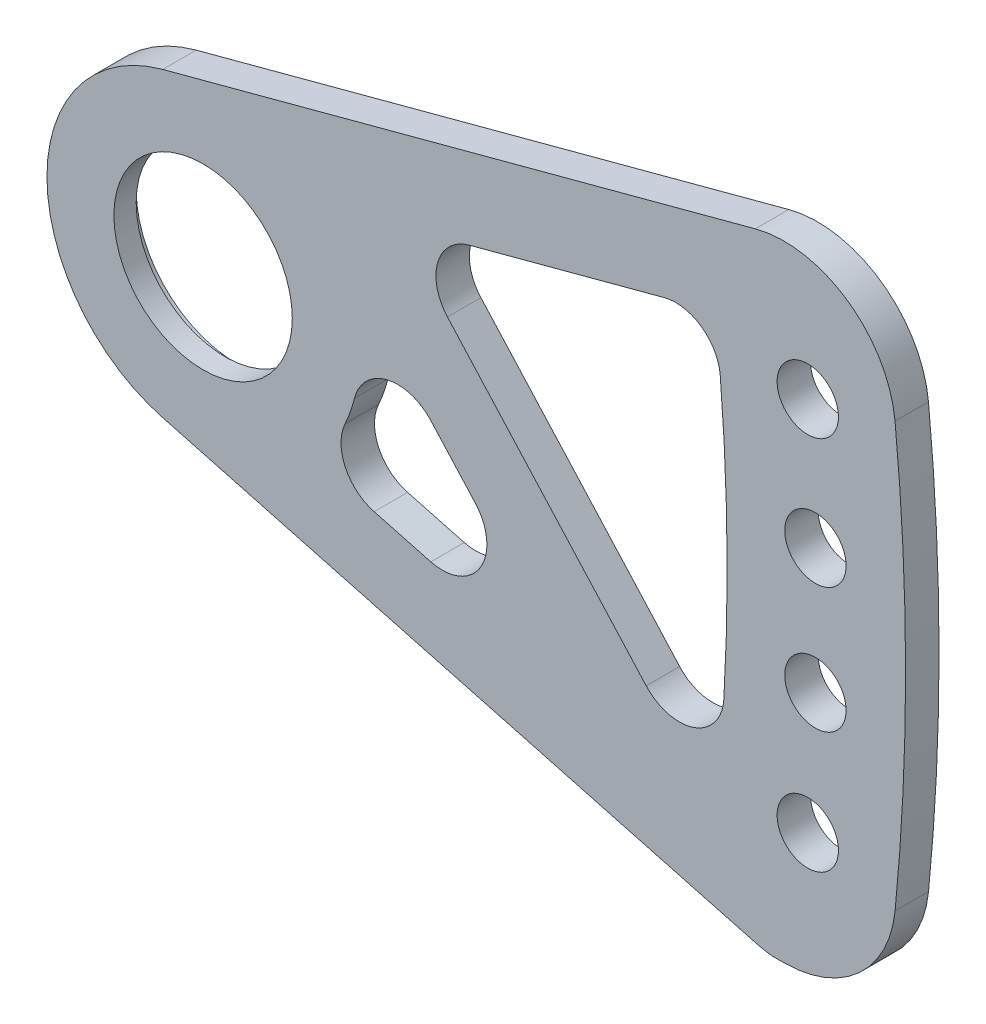
SolidWorks part; units mm, degrees
material "Сплав 2024"
ref_plane "Спереди" through (0, 0, 0) normal (0, 0, 1) x (1, 0, 0)
ref_plane "Сверху" through (0, 0, 0) normal (0, 1, 0) x (1, 0, 0)
ref_plane "Справа" through (0, 0, 0) normal (1, 0, 0) x (0, 0, -1)
sketch "Эскиз1" plane through (0, 0, 0) normal (0, 0, 1) x (1, 0, 0)
  line L0 (-31.9542, -25) -> (253.1565, -25) construction
  line L1 (9, 35.6094) -> (9, -47.5785) construction
  line L2 (-39.2405, -28) -> (262.4545, -28) construction
  line L3 (-31.9542, -22) -> (262.4545, -22) construction
  line L4 (-9.5085, -3.0964) -> (-1.3987, -28)
  line L5 (8.3266, 5.5379) -> (20.6752, -13.0291)
  line L6 (-26.4187, 0) -> (187.6558, 0) construction
  line L7 (121.0002, 11.4893) -> (83.7656, -14.4365)
  line L8 (63.7181, -22) -> (35.7314, -22)
  line L9 (0, 0) -> (183.9142, 5.6191) construction
  line L10 (0, 0) -> (183.9142, -5.6191) construction
  line L11 (0, 0) -> (183.2281, -16.8363) construction
  line L12 (0, 0) -> (183.2281, 16.8363) construction
  line L13 (125.388, 13.526) -> (189.5368, 30.6561)
  line L14 (-1.3987, -28) -> (189.9474, -28)
  line L15 (40.5, -17.0585) -> (40.5, -35.954) construction
  line L16 (72, -17.0585) -> (72, -35.954) construction
  line L17 (20.6752, -13.0291) -> (35.7314, -22)
  line L18 (83.7656, -14.4365) -> (63.7181, -22)
  arc A0 (8.3266, 5.5379) -> (-9.5085, -3.0964) centre (0, 0) ccw
  circle A1 centre (129, 0) radius 8
  arc A2 (125.388, 13.526) -> (121.0002, 11.4893) centre (129, 0) ccw
  circle A3 centre (0, 0) radius 184 construction
  arc A4 (189.9474, -28) -> (189.5368, 30.6561) centre (0, 0) ccw
  dimension "D1" = 20
  dimension "D2" = 25
  dimension "D3" = 9
  dimension "D6" = 16
  dimension "D8" = 28
  dimension "D9" = 368
  dimension "D10" = 31.5
  dimension "D16" = 192
  dimension "D4" = 6
  dimension "D5" = 3
  dimension "D7" = 129
  dimension "D11" = 3.5
  dimension "D12" = 3.5
  dimension "D13" = 3.5
  dimension "D14" = 1.75
  dimension "D15" = 31.5
extrude "Бобышка-Вытянуть1" add sketch "Эскиз1" along normal blind 3
hole_wizard "Отверстие с зазором M31" positions "Эскиз3" profile "Эскиз2" hole size "M3" standard "Ansi Metric" end condition through all
sketch "Эскиз3" plane through (0, 0, 3) normal (0, 0, 1) x (1, 0, 0)
  line L0 (-31.9542, -25) -> (253.1565, -25) construction
  line L1 (9, 35.6094) -> (9, -47.5785) construction
  line L2 (40.5, -17.0585) -> (40.5, -35.954) construction
  line L3 (72, -17.0585) -> (72, -35.954) construction
  point P0 (9, -25)
  point P6 (40.5, -25)
  point P10 (72, -25)
sketch "Эскиз2" plane through (9, -25, 3) normal (1, 0, 0) x (0, -1, 0)
  line L0 (0, 0) -> (0, 3)
  line L1 (0, 3) -> (1.7, 3)
  line L2 (1.7, 3) -> (1.7, 0)
  line L5 (1.7, 0) -> (0, 0)
  line L11 (0, -6.35) -> (0, 107.95) construction
  dimension "Диаметр сквозного отверстия" = 3.4
  dimension "Глубина сквозного отверстия" = 3
hole_wizard "Отверстие с зазором M51" positions "Эскиз5" profile "Эскиз4" hole size "M5" standard "Ansi Metric" end condition through all
sketch "Эскиз5" plane through (0, 0, 3) normal (0, 0, 1) x (1, 0, 0)
  point P2 (0, 0)
sketch "Эскиз4" plane through (0, 0, 3) normal (1, 0, 0) x (0, -1, 0)
  line L0 (0, 0) -> (0, 3)
  line L1 (0, 3) -> (2.75, 3)
  line L2 (2.75, 3) -> (2.75, 0)
  line L5 (2.75, 0) -> (0, 0)
  line L11 (0, -6.35) -> (0, 107.95) construction
  dimension "Диаметр сквозного отверстия" = 5.5
  dimension "Глубина сквозного отверстия" = 3
hole_wizard "Отверстие с зазором M52" positions "Эскиз7" profile "Эскиз6" hole size "M5" standard "Ansi Metric" end condition through all
sketch "Эскиз7" plane through (0, 0, 3) normal (0, 0, 1) x (1, 0, 0)
  point P0 (183.2281, 16.8363)
  point P3 (183.9142, 5.6191)
  point P6 (183.9142, -5.6191)
  point P9 (183.2281, -16.8363)
sketch "Эскиз6" plane through (183.2281, 16.8363, 3) normal (1, 0, 0) x (0, -1, 0)
  line L0 (0, 0) -> (0, 3)
  line L1 (0, 3) -> (2.75, 3)
  line L2 (2.75, 3) -> (2.75, 0)
  line L5 (2.75, 0) -> (0, 0)
  line L11 (0, -6.35) -> (0, 107.95) construction
  dimension "Диаметр сквозного отверстия" = 5.5
  dimension "Глубина сквозного отверстия" = 3
fillet "Скругление1" radius 10 6 edges at (35.7314, -22, 1.5) (20.6752, -13.0291, 1.5) (63.7181, -22, 1.5) (83.7656, -14.4365, 1.5) (189.9474, -28, 1.5) (189.5368, 30.6561, 1.5)
fillet "Скругление2" radius 5 1 edges at (-1.3987, -28, 1.5)
sketch "Эскиз8" plane through (0, 0, 3) normal (0, 0, 1) x (1, 0, 0)
  line L0 (138.9079, 9.8911) -> (175.4042, 19.6369)
  line L1 (178.5224, 27.7149) -> (125.388, 13.526) construction
  line L2 (142.9717, -0.889) -> (175.2463, -21)
  line L3 (175.2463, -21) -> (132.5, -21)
  line L4 (2.2315, -28) -> (181.1077, -28) construction
  line L5 (115.0501, -1.1834) -> (86.5894, -21)
  line L6 (121.0002, 11.4893) -> (84.7863, -13.7258) construction
  line L8 (125.5, -13.5554) -> (125.5, -21)
  line L9 (132.5, -13.5554) -> (132.5, -21)
  line L10 (138.9079, 9.8911) -> (176.0039, -13.2243)
  line L11 (125.5, -21) -> (86.5894, -21)
  arc A0 (115.0501, -1.1834) -> (125.5, -13.5554) centre (129, 0) ccw
  arc A1 (125.388, 13.526) -> (121.0002, 11.4893) centre (129, 0) ccw construction
  arc A2 (176.0039, -13.2243) -> (175.4042, 19.6369) centre (0, 0) ccw
  arc A3 (132.5, -13.5554) -> (142.9717, -0.889) centre (129, 0) ccw
  dimension "D2" = 353
  dimension "D1" = 7
  dimension "D3" = 7
  dimension "D4" = 7
  dimension "D5" = 7
  dimension "D6" = 3.5
  dimension "D7" = 7
extrude "Вырез-Вытянуть1" [suppressed] cut sketch "Эскиз8" against normal through all
fillet "Скругление3" [suppressed] radius 4
sketch "Эскиз9" plane through (0, 0, 0) normal (0, 0, -1) x (-1, 0, 0)
  circle A0 centre (-129, 0) radius 9
  dimension "D1" = 18
extrude "Вырез-Вытянуть2" cut sketch "Эскиз9" against normal blind 1
sketch "Эскиз10" plane through (0, 0, 3) normal (0, 0, 1) x (1, 0, 0)
  line L0 (6.5, -25) -> (11.5, -25) construction
  line L1 (6.5, -23.3) -> (11.5, -23.3)
  line L2 (6.5, -26.7) -> (11.5, -26.7)
  line L3 (38, -25) -> (43, -25) construction
  line L4 (38, -23.3) -> (43, -23.3)
  line L5 (38, -26.7) -> (43, -26.7)
  line L6 (69.5, -25) -> (74.5, -25) construction
  line L7 (69.5, -23.3) -> (74.5, -23.3)
  line L8 (69.5, -26.7) -> (74.5, -26.7)
  arc A0 (6.5, -23.3) -> (6.5, -26.7) centre (6.5, -25) ccw
  arc A1 (11.5, -26.7) -> (11.5, -23.3) centre (11.5, -25) ccw
  circle A2 centre (9, -25) radius 1.7 construction
  arc A3 (38, -23.3) -> (38, -26.7) centre (38, -25) ccw
  arc A4 (43, -26.7) -> (43, -23.3) centre (43, -25) ccw
  circle A5 centre (40.5, -25) radius 1.7 construction
  arc A6 (69.5, -23.3) -> (69.5, -26.7) centre (69.5, -25) ccw
  arc A7 (74.5, -26.7) -> (74.5, -23.3) centre (74.5, -25) ccw
  circle A8 centre (72, -25) radius 1.7 construction
  point P2 (9, -25)
  point P12 (40.5, -25)
  point P22 (72, -25)
  dimension "D1" = 5
  dimension "D2" = 5
  dimension "D3" = 5
extrude "Вырез-Вытянуть3" cut sketch "Эскиз10" against normal through all
sketch "Эскиз11" plane through (0, 0, 0) normal (0, 0, 1) x (1, 0, 0)
  line L0 (192, 41.8956) -> (192, -28) construction
  line L1 (192, -28) -> (188.2804, -28) construction
  line L2 (2.2315, -28) -> (181.1077, -28) construction
  line L3 (-10, 21.326) -> (-10, -31.1704) construction
  line L4 (142.753, 28.0534) -> (192, 28.0534) construction
  arc A0 (191.0587, -18.989) -> (191.0531, 19.0454) centre (0, 0) ccw construction
  arc A1 (8.3266, 5.5379) -> (-9.5085, -3.0964) centre (0, 0) ccw construction
  arc A2 (191.0531, 19.0454) -> (178.5224, 27.7149) centre (181.1024, 18.0534) ccw construction
sketch "Эскиз12" plane through (0, 0, 0) normal (0, 0, -1) x (-1, 0, 0)
  line L0 (-178.5224, -27.7149) -> (-125.388, -13.526)
  line L1 (-129, 0) -> (-194.8656, 0) construction
  line L2 (-191.0531, -19.0454) -> (-194.8656, -30.0785)
  line L3 (-194.8656, -30.0785) -> (9.1858, -30.0785)
  line L4 (9.1858, -30.0785) -> (17.7085, 18.6906)
  line L5 (17.7085, 18.6906) -> (-125.388, 13.526)
  arc A0 (-125.388, 13.526) -> (-125.388, -13.526) centre (-129, 0) cw
  arc A3 (-178.5224, -27.7149) -> (-191.0531, -19.0454) centre (-181.1024, -18.0534) cw
extrude "Вырез-Вытянуть4" cut sketch "Эскиз12" against normal through all
sketch "Эскиз13" plane through (0, 0, 0) normal (0, 0, -1) x (-1, 0, 0)
  line L0 (-174.9157, 19.5065) -> (-138.9079, 9.8911)
  line L1 (-174.9157, -19.5065) -> (-138.9079, -9.8911)
  line L2 (-178.5224, 27.7149) -> (-125.388, 13.526) construction
  line L3 (-125.388, -13.526) -> (-178.5224, -27.7149) construction
  line L4 (-129, 0) -> (-195.6005, 0) construction
  line L5 (-175.9652, 3.5) -> (-142.5554, 3.5)
  line L6 (-142.5554, -3.5) -> (-175.9652, -3.5)
  arc A0 (-175.9652, -3.5) -> (-174.9157, -19.5065) centre (0, 0) ccw
  arc A1 (-138.9079, 9.8911) -> (-142.5554, 3.5) centre (-129, 0) ccw
  arc A2 (-142.5554, -3.5) -> (-138.9079, -9.8911) centre (-129, 0) ccw
  arc A3 (-174.9157, 19.5065) -> (-175.9652, 3.5) centre (0, 0) ccw
  dimension "D2" = 14
  dimension "D1" = 176
  dimension "D3" = 7
  dimension "D4" = 7
  dimension "D5" = 3.5
  dimension "D6" = 3.5
extrude "Вырез-Вытянуть5" [suppressed] cut sketch "Эскиз13" against normal through all
fillet "Скругление4" [suppressed] radius 4
fillet "Скругление5" [suppressed] radius 4
sketch "Эскиз14" plane through (0, 0, 0) normal (0, 0, -1) x (-1, 0, 0)
  line L0 (-174.9157, 19.5065) -> (-146.5265, 11.9255)
  line L1 (-174.9157, -19.5065) -> (-144.5533, -11.3986) construction
  line L2 (-178.5224, 27.7149) -> (-125.388, 13.526) construction
  line L3 (-125.388, -13.526) -> (-178.5224, -27.7149) construction
  line L4 (-174.9157, -19.5065) -> (-146.5265, 11.9255)
  line L5 (-139.3896, 9.3838) -> (-162.4851, -16.187)
  line L6 (-162.4851, -16.187) -> (-138.9079, -9.8911)
  arc A1 (-139.3896, 9.3838) -> (-138.9079, -9.8911) centre (-129, 0) ccw
  arc A3 (-174.9157, 19.5065) -> (-174.9157, -19.5065) centre (0, 0) ccw
  dimension "D1" = 176
  dimension "D3" = 14
  dimension "D2" = 7
  dimension "D4" = 7
  dimension "D5" = 7
extrude "Вырез-Вытянуть6" cut sketch "Эскиз14" against normal through all
fillet "Скругление6" radius 4 6 edges at (139.3896, 9.3838, 1.5) (138.9079, -9.8911, 1.5) (162.4851, -16.187, 1.5) (146.5265, 11.9255, 1.5) (174.9157, -19.5065, 1.5) (174.9157, 19.5065, 1.5)
equation "\"D12@Эскиз1\"=\"D11@Эскиз1\""
equation "\"D13@Эскиз1\"=\"D11@Эскиз1\""
equation "\"D14@Эскиз1\"=\"D11@Эскиз1\"/2"
